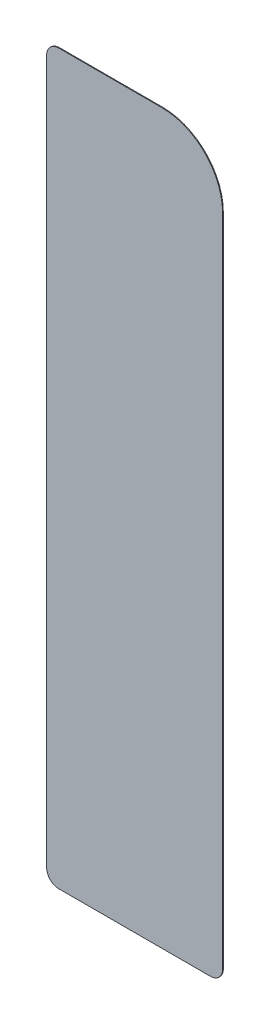
SolidWorks part; units mm, degrees
material "Melinex 454"
ref_plane "Front Plane" through (0, 0, 0) normal (0, 0, 1) x (1, 0, 0)
ref_plane "Top Plane" through (0, 0, 0) normal (0, 1, 0) x (1, 0, 0)
ref_plane "Right Plane" through (0, 0, 0) normal (1, 0, 0) x (0, 0, -1)
other "Configuration Table"
sketch "Sketch17" plane through (0, 0, 0) normal (0, 0, 1) x (1, 0, 0)
  line L0 (0, 60) -> (0, -60) construction
  line L1 (-12.5, 60) -> (4.5, 60)
  line L2 (-14.5, 58) -> (-14.5, -58)
  line L3 (-12.5, -60) -> (12.5, -60)
  line L4 (14.5, 50) -> (14.5, -58)
  line L5 (-14.5, 60) -> (14.5, -60) construction
  line L6 (-14.5, -60) -> (14.5, 60) construction
  line L7 (-14.5, 0) -> (14.5, 0) construction
  line L8 (0, -55) -> (0, 55) construction
  arc A0 (-14.5, -58) -> (-12.5, -60) centre (-12.5, -58) ccw
  arc A1 (12.5, -60) -> (14.5, -58) centre (12.5, -58) ccw
  arc A2 (4.5, 60) -> (14.5, 50) centre (4.5, 50) cw
  arc A3 (-12.5, 60) -> (-14.5, 58) centre (-12.5, 58) ccw
  point P0 (0, 0)
extrude "Boss-Extrude6" add sketch "Sketch17" along normal blind 0.125
